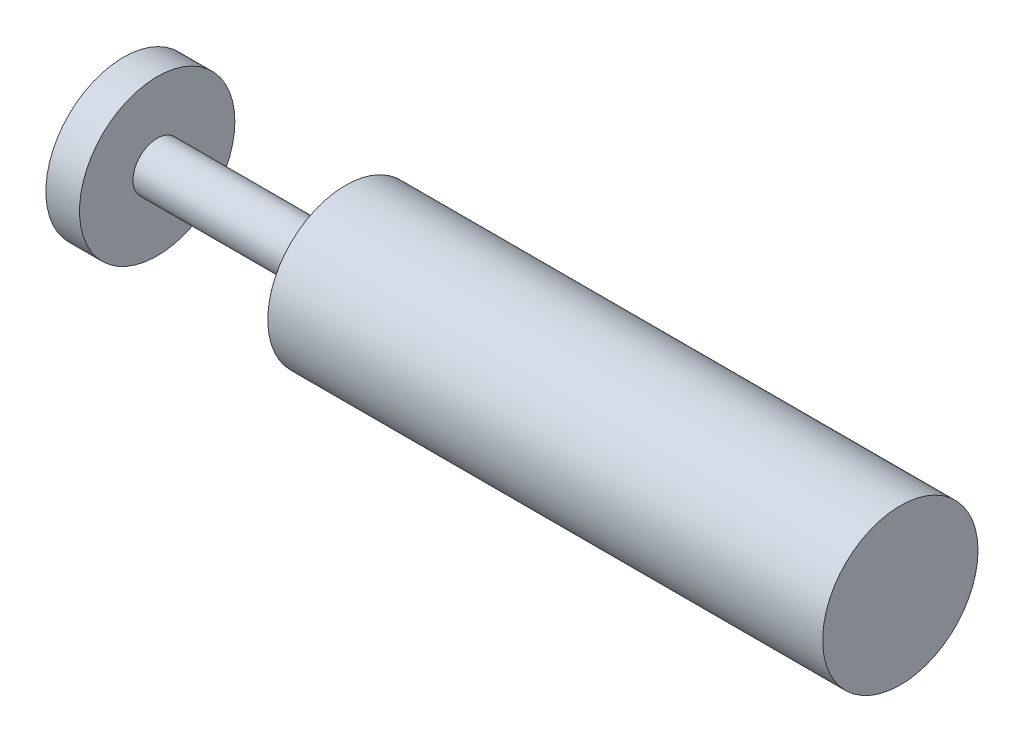
SolidWorks part; units mm, degrees
ref_plane "Front Plane" through (0, 0, 0) normal (0, 0, 1) x (1, 0, 0)
ref_plane "Top Plane" through (0, 0, 0) normal (0, 1, 0) x (1, 0, 0)
ref_plane "Right Plane" through (0, 0, 0) normal (1, 0, 0) x (0, 0, -1)
sketch "Sketch1" plane through (0, 0, 0) normal (0, 1, 0) x (1, 0, 0)
  line L0 (0, 0) -> (0, 7)
  line L1 (0, 7) -> (3.0318, 7)
  line L2 (3.0318, 7) -> (3.0318, 2.1847)
  line L3 (3.0318, 2.1847) -> (20, 2.1847)
  line L4 (20, 2.1847) -> (20, 7)
  line L5 (20, 7) -> (70, 7)
  line L6 (70, 7) -> (70, 0)
  line L7 (70, 0) -> (0, 0)
  dimension "D1" = 7
  dimension "D2" = 20
  dimension "D3" = 70
revolve "Revolve1" add sketch "Sketch1" angle 360 about L7
